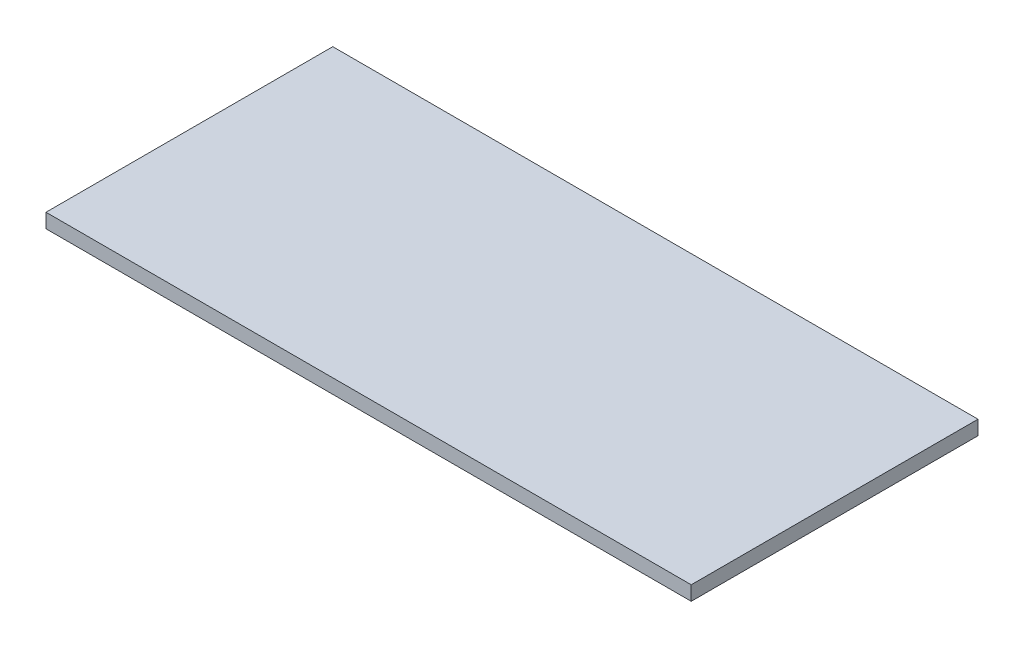
SolidWorks part; units mm, degrees
ref_plane "Front Plane" through (0, 0, 0) normal (0, 0, 1) x (1, 0, 0)
ref_plane "Top Plane" through (0, 0, 0) normal (0, 1, 0) x (1, 0, 0)
ref_plane "Right Plane" through (0, 0, 0) normal (1, 0, 0) x (0, 0, -1)
sketch "Sketch1" plane through (0, 0, 0) normal (0, 1, 0) x (1, 0, 0)
  line L1 (-450, 200) -> (450, 200)
  line L2 (-450, 200) -> (-450, -200)
  line L3 (-450, -200) -> (450, -200)
  line L4 (450, 200) -> (450, -200)
  line L5 (-450, 200) -> (450, -200) construction
  line L6 (-450, -200) -> (450, 200) construction
  point P0 (0, 0)
  dimension "D1" = 900
  dimension "D2" = 400
extrude "Boss-Extrude1" add sketch "Sketch1" along normal blind 20
